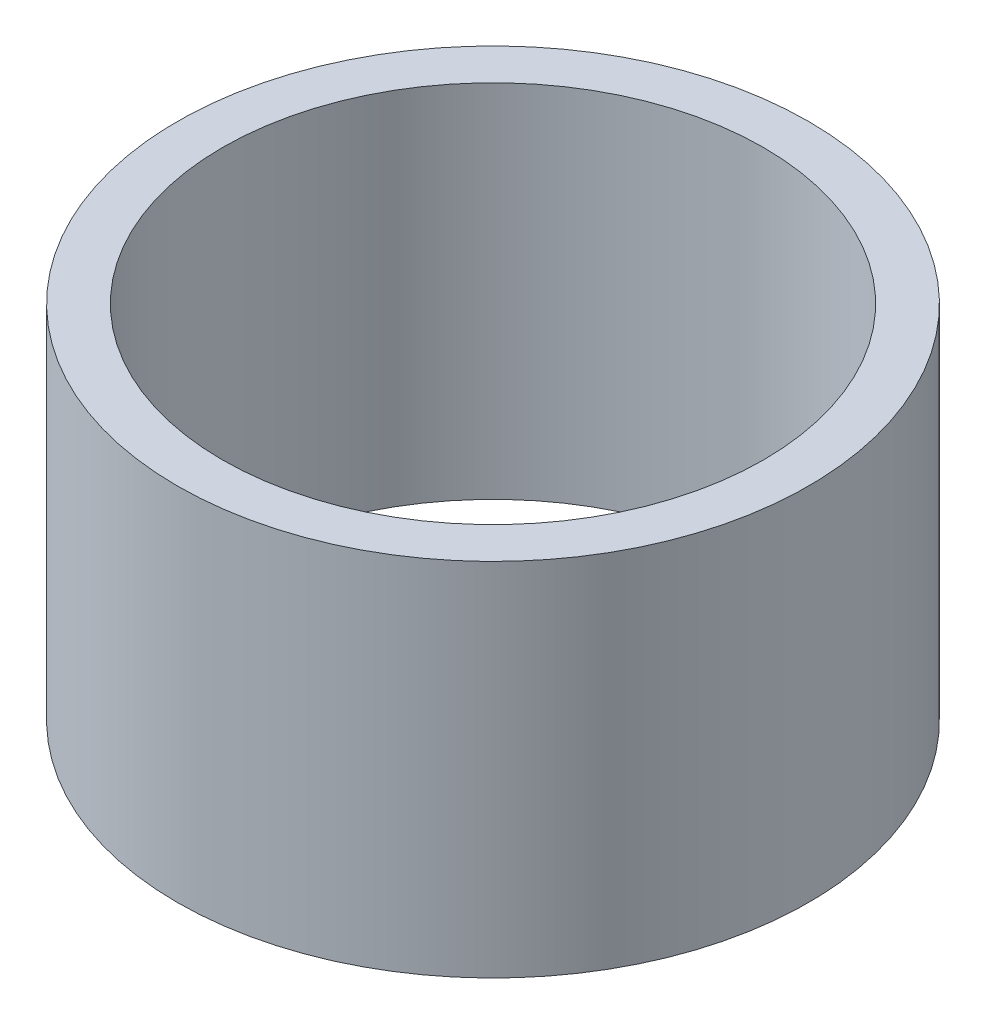
SolidWorks part; units mm, degrees
ref_plane "Front Plane" through (0, 0, 0) normal (0, 0, 1) x (1, 0, 0)
ref_plane "Top Plane" through (0, 0, 0) normal (0, 1, 0) x (1, 0, 0)
ref_plane "Right Plane" through (0, 0, 0) normal (1, 0, 0) x (0, 0, -1)
sketch "Sketch1" plane through (0, 0, 0) normal (0, 1, 0) x (1, 0, 0)
  circle A0 centre (0, 0) radius 22.225
  dimension "D1" = 44.45
extrude "Boss-Extrude1" add sketch "Sketch1" along normal blind 25.4 contours A0
sketch "Sketch4" plane through (0, 25.4, 0) normal (0, 1, 0) x (1, 0, 0)
  circle A0 centre (0, 0) radius 19.05
  dimension "D1" = 38.1
extrude "Cut-Extrude1" cut sketch "Sketch4" against normal through all
